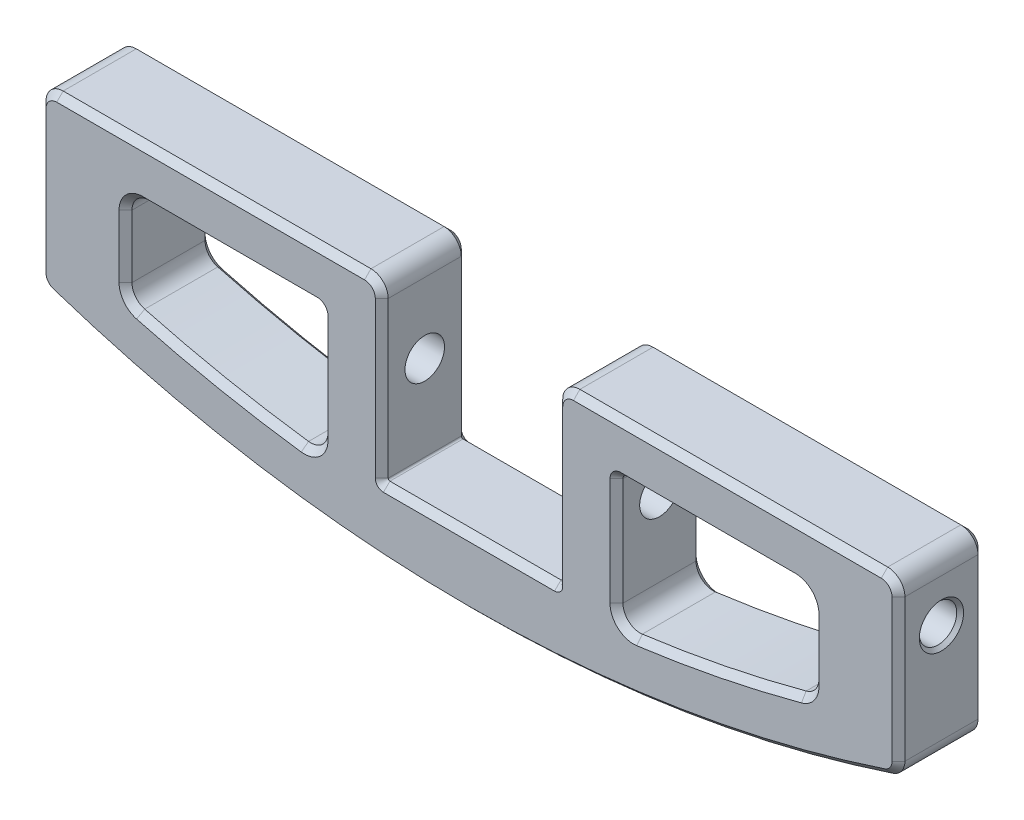
SolidWorks part; units mm, degrees
ref_plane "Front" through (0, 0, 0) normal (0, 0, 1) x (1, 0, 0)
ref_plane "Top" through (0, 0, 0) normal (0, 1, 0) x (1, 0, 0)
ref_plane "Right" through (0, 0, 0) normal (1, 0, 0) x (0, 0, -1)
sketch "Skizze1" plane through (0, 0, 0) normal (0, 0, 1) x (1, 0, 0)
  line L0 (0, 0) -> (0, -31.6253) construction
  line L1 (0, 0) -> (32.2456, 0) construction
  line L2 (10.15, 0) -> (10.15, -20.3)
  line L3 (10.15, -20.3) -> (-10.15, -20.3)
  line L4 (49.95, 0) -> (49.95, -20)
  line L5 (10.15, 0) -> (49.95, 0)
  line L7 (-10.15, 0) -> (-49.95, 0)
  line L8 (-49.95, 0) -> (-49.95, -20)
  line L9 (-10.15, 0) -> (-10.15, -20.3)
  line L10 (17.15, -6) -> (17.15, -21.306)
  line L11 (17.15, -6) -> (39.95, -6)
  line L12 (39.95, -6) -> (39.95, -16.8235)
  line L13 (-17.15, -6) -> (-39.95, -6)
  line L14 (-39.95, -6) -> (-39.95, -16.8235)
  line L15 (-17.15, -6) -> (-17.15, -21.306)
  arc A0 (49.95, -20) -> (0, -28.3) centre (0, 126.1514) cw
  arc A1 (-49.95, -20) -> (0, -28.3) centre (0, 126.1514) ccw
  arc A2 (39.95, -16.8235) -> (17.15, -21.306) centre (0, 126.1514) cw
  arc A3 (-39.95, -16.8235) -> (-17.15, -21.306) centre (0, 126.1514) ccw
  point P16 (0, -20.3)
  point P21 (0, 0)
  dimension "D6" = 6
  dimension "D1" = 20.3
  dimension "D2" = 20.3
  dimension "D3" = 99.9
  dimension "D4" = 8
  dimension "D5" = 20
  dimension "D7" = 6
  dimension "D8" = 7
  dimension "D9" = 10
extrude "Aufsatz-Linear austragen1" add sketch "Skizze1" along normal blind 10
sketch "Skizze2" plane through (49.95, 0, 0) normal (1, 0, 0) x (0, 0, -1)
  line L0 (-5, 0) -> (-5, -13.0249) construction
  line L1 (-10, 0) -> (0, 0) construction
  circle A0 centre (-5, -7) radius 2.175
  dimension "D1" = 7
  dimension "D2" = 4.35
extrude "Schnitt-Linear austragen1" cut sketch "Skizze2" against normal blind 8
mirror "Spiegeln1" about plane through (0, 0, 0) normal (1, 0, 0) of "Schnitt-Linear austragen1"
sketch "Skizze3" plane through (10.15, 0, 0) normal (-1, 0, 0) x (0, 0, 1)
  line L0 (5, 0) -> (5, -20.3) construction
  line L1 (10, 0) -> (0, 0) construction
  line L3 (10, -20.3) -> (0, -20.3) construction
  circle A0 centre (5, -10.15) radius 2.3
  dimension "D1" = 4.6
extrude "Schnitt-Linear austragen2" cut sketch "Skizze3" against normal blind 10 and the other way blind 30
fillet "Verrundung1" radius 2 12 edges at (49.95, 0, 5) (-17.15, -21.306, 5) (-39.95, -16.8235, 5) (-39.95, -6, 5) (39.95, -6, 5) (39.95, -16.8235, 5) (17.15, -21.306, 5) (10.15, 0, 5) (-10.15, 0, 5) (-49.95, 0, 5) (-49.95, -20, 5) (49.95, -20, 5)
fillet "Verrundung2" radius 0.2 2 edges at (-10.15, -20.3, 5) (10.15, -20.3, 5)
fillet "Verrundung3" radius 0.5 2 edges at (-17.15, -6, 5) (17.15, -6, 5)
chamfer "Fase1" distance 0.75 angle 45 64 edges at (-39.3642, -6.5858, 0) (-27.8, -6, 0) (-17.2964, -6.1464, 0) (-17.15, -12.7713, 0) (-17.8315, -20.5464, 0) (-29.0021, -19.4395, 0) (-39.5369, -16.5148, 0) (-39.95, -11.6488, 0) (39.3642, -6.5858, 0) (39.95, -11.6488, 0) (39.5369, -16.5148, 0) (29.0021, -19.4395, 0) (17.8315, -20.5464, 0) (17.15, -12.7713, 0) (17.2964, -6.1464, 0) (27.8, -6, 0) (10.7358, -0.5858, 0) (10.15, -11.05, 0) (10.0914, -20.2414, 0) (0, -20.3, 0) (-10.0914, -20.2414, 0) (-10.15, -11.05, 0) (-10.7358, -0.5858, 0) (-30.05, 0, 0) (-49.3642, -0.5858, 0) (-49.95, -10.2814, 0) (-49.5714, -19.7338, 0) (0, -28.3, 0) (49.5714, -19.7338, 0) (49.95, -10.2814, 0) (49.3642, -0.5858, 0) (30.05, 0, 0) (-17.2964, -6.1464, 10) (-27.8, -6, 10) (-39.3642, -6.5858, 10) (-39.95, -11.6488, 10) (-39.5369, -16.5148, 10) (-29.0021, -19.4395, 10) (-17.8315, -20.5464, 10) (-17.15, -12.7713, 10) (49.5714, -19.7338, 10) (0, -28.3, 10) (-49.5714, -19.7338, 10) (-49.95, -10.2814, 10) (-49.3642, -0.5858, 10) (-30.05, 0, 10) (-10.7358, -0.5858, 10) (-10.15, -11.05, 10) (-10.0914, -20.2414, 10) (0, -20.3, 10) (10.0914, -20.2414, 10) (10.15, -11.05, 10) (10.7358, -0.5858, 10) (30.05, 0, 10) (49.3642, -0.5858, 10) (49.95, -10.2814, 10) (39.3642, -6.5858, 10) (27.8, -6, 10) (17.2964, -6.1464, 10) (17.15, -12.7713, 10) (17.8315, -20.5464, 10) (29.0021, -19.4395, 10) (39.5369, -16.5148, 10) (39.95, -11.6488, 10)
chamfer "Fase2" distance 0.4 angle 45 2 edges at (-49.95, -7, 2.825) (49.95, -7, 2.825)
